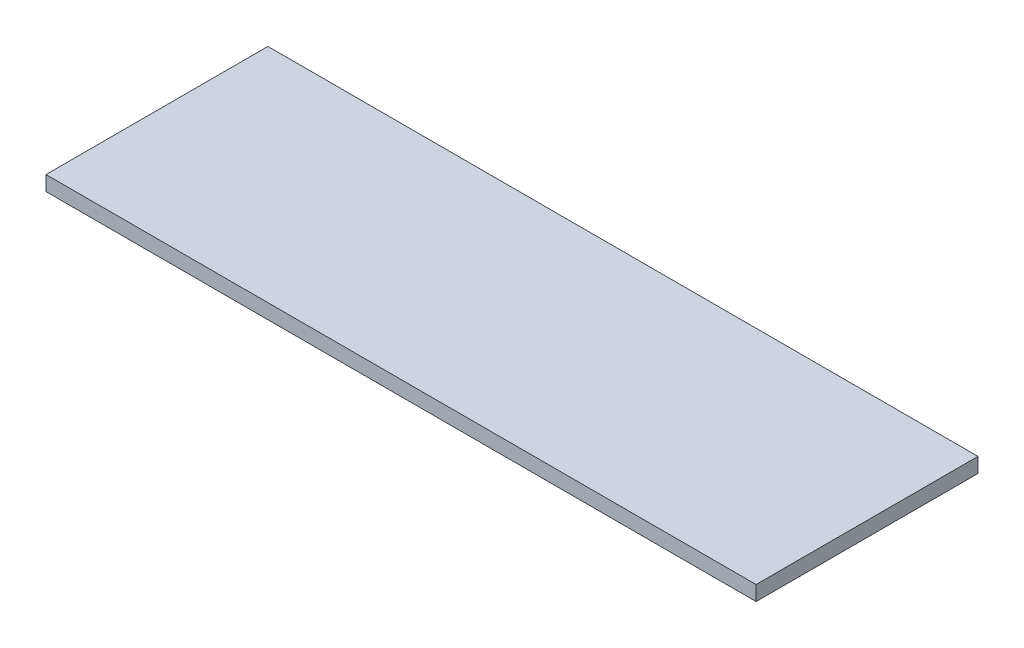
SolidWorks part; units mm, degrees
ref_plane "前视基准面" through (0, 0, 0) normal (0, 0, 1) x (1, 0, 0)
ref_plane "上视基准面" through (0, 0, 0) normal (0, 1, 0) x (1, 0, 0)
ref_plane "右视基准面" through (0, 0, 0) normal (1, 0, 0) x (0, 0, -1)
sketch "草图1" plane through (0, 0, 0) normal (0, 1, 0) x (1, 0, 0)
  line L0 (0, 0) -> (288, 0)
  line L1 (288, 0) -> (288, 90)
  line L2 (288, 90) -> (0, 90)
  line L3 (0, 90) -> (0, 0)
extrude "凸台-拉伸1" add sketch "草图1" along normal blind 6
